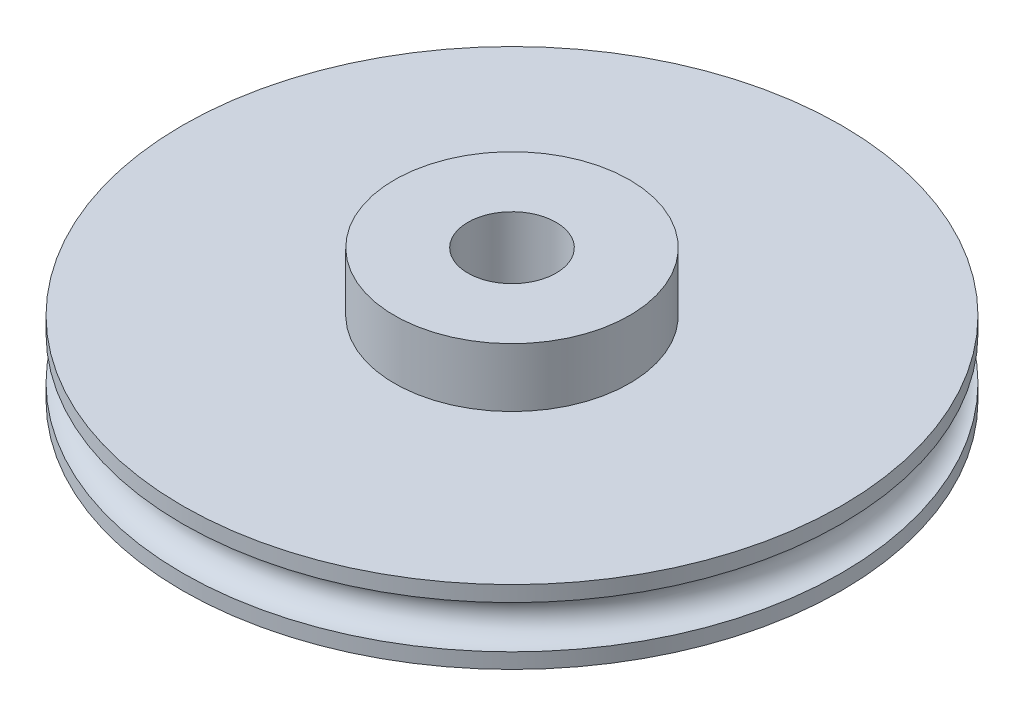
SolidWorks part; units mm, degrees
ref_plane "Plan de face" through (0, 0, 0) normal (0, 0, 1) x (1, 0, 0)
ref_plane "Plan de dessus" through (0, 0, 0) normal (0, 1, 0) x (1, 0, 0)
ref_plane "Plan de droite" through (0, 0, 0) normal (1, 0, 0) x (0, 0, -1)
sketch "Esquisse1" plane through (0, 0, 0) normal (0, 0, 1) x (1, 0, 0)
  line L0 (22.42, 1.0373) -> (22.42, 0)
  line L1 (3, 0) -> (23.97, 0)
  line L2 (3, 0) -> (3, 5)
  line L3 (8, 5) -> (23.97, 5)
  line L4 (0, 0) -> (0, 26.6549)
  line L6 (3, 5) -> (3, 9)
  line L7 (3, 9) -> (8, 9)
  line L8 (8, 5) -> (8, 9)
  line L9 (22.42, 5) -> (23.97, 5)
  line L10 (22.42, 5) -> (22.42, 3.9373)
  line L11 (22.42, 0) -> (23.97, 0)
  arc A0 (22.42, 3.9373) -> (22.42, 1.0373) centre (22.42, 2.4873) ccw
  dimension "D6" = 2.9
  dimension "D1" = 5
  dimension "D2" = 3
  dimension "D3" = 4
  dimension "D4" = 5
  dimension "D5" = 22.42
revolve "Révolution1" add sketch "Esquisse1" angle 360 about L4
